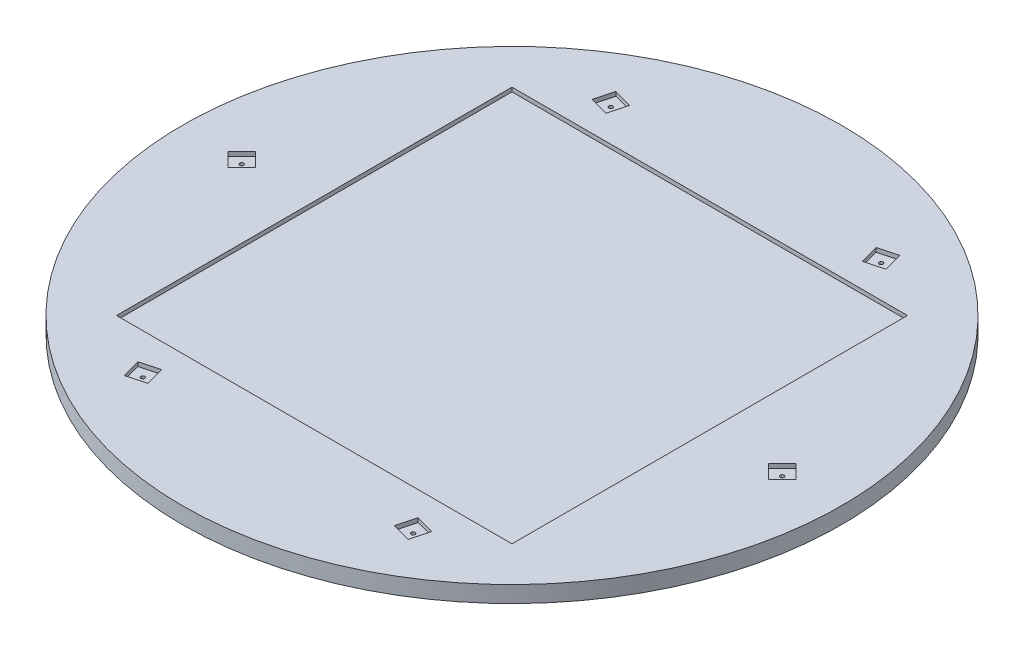
SolidWorks part; units mm, degrees
material "Balsa"
ref_plane "Front Plane" through (0, 0, 0) normal (0, 0, 1) x (1, 0, 0)
ref_plane "Top Plane" through (0, 0, 0) normal (0, 1, 0) x (1, 0, 0)
ref_plane "Right Plane" through (0, 0, 0) normal (1, 0, 0) x (0, 0, -1)
sketch "Sketch1" plane through (0, 0, 0) normal (0, 1, 0) x (1, 0, 0)
  circle A0 centre (0, 0) radius 254
  dimension "D1" = 508
extrude "Boss-Extrude1" add sketch "Sketch1" along normal blind 12.7
sketch "Sketch2" plane through (0, 12.7, 0) normal (0, 1, 0) x (1, 0, 0)
  line L1 (-152.4, -152.4) -> (152.4, -152.4)
  line L2 (-152.4, -152.4) -> (-152.4, 152.4)
  line L3 (-152.4, 152.4) -> (152.4, 152.4)
  line L4 (152.4, -152.4) -> (152.4, 152.4)
  line L5 (-152.4, -152.4) -> (152.4, 152.4) construction
  line L6 (-152.4, 152.4) -> (152.4, -152.4) construction
  point P0 (0, 0)
  dimension "D1" = 304.8
  dimension "D2" = 304.8
extrude "Cut-Extrude1" cut sketch "Sketch2" against normal blind 3.175
sketch "Sketch3" plane through (0, 12.7, 0) normal (0, 1, 0) x (1, 0, 0)
  line L0 (0, 0) -> (104.14, 180.3758) construction
  line L6 (94.9544, 185.6791) -> (113.3256, 175.0725) construction
  line L7 (98.8367, 171.1902) -> (94.9544, 185.6791)
  line L27 (94.9544, 185.6791) -> (109.4433, 189.5614)
  line L28 (109.4433, 189.5614) -> (113.3256, 175.0725)
  line L29 (113.3256, 175.0725) -> (98.8367, 171.1902)
  line L30 (109.4433, 189.5614) -> (98.8367, 171.1902) construction
  line L31 (208.28, 10.6066) -> (218.8866, 0)
  line L32 (197.6734, 0) -> (208.28, 10.6066)
  line L33 (218.8866, 0) -> (208.28, -10.6066)
  line L34 (208.28, -10.6066) -> (197.6734, 0)
  line L35 (113.3256, -175.0725) -> (109.4433, -189.5614)
  line L36 (98.8367, -171.1902) -> (113.3256, -175.0725)
  line L37 (109.4433, -189.5614) -> (94.9544, -185.6791)
  line L38 (94.9544, -185.6791) -> (98.8367, -171.1902)
  line L39 (-94.9544, -185.6791) -> (-109.4433, -189.5614)
  line L40 (-98.8367, -171.1902) -> (-94.9544, -185.6791)
  line L41 (-109.4433, -189.5614) -> (-113.3256, -175.0725)
  line L42 (-113.3256, -175.0725) -> (-98.8367, -171.1902)
  line L43 (-208.28, -10.6066) -> (-218.8866, 0)
  line L44 (-197.6734, 0) -> (-208.28, -10.6066)
  line L45 (-218.8866, 0) -> (-208.28, 10.6066)
  line L46 (-208.28, 10.6066) -> (-197.6734, 0)
  line L47 (-113.3256, 175.0725) -> (-109.4433, 189.5614)
  line L48 (-98.8367, 171.1902) -> (-113.3256, 175.0725)
  line L49 (-109.4433, 189.5614) -> (-94.9544, 185.6791)
  line L50 (-94.9544, 185.6791) -> (-98.8367, 171.1902)
  point P5 (104.14, 180.3758)
  point P6 (104.14, 180.3758)
  point P11 (-101.208, 212.9416)
  point P30 (0, 0)
  point P32 (0, 0)
  point P42 (0, 0)
  dimension "D1" = 208.28
  dimension "D2" = 15
  dimension "D3" = 60
  dimension "D4" = 6
extrude "Cut-Extrude2" cut sketch "Sketch3" against normal blind 3.175
sketch "Sketch4" plane through (0, 12.7, 0) normal (0, 1, 0) x (1, 0, 0)
  line L0 (104.14, 180.3758) -> (102.1989, 187.6202) construction
  line L1 (94.9544, 185.6791) -> (109.4433, 189.5614) construction
  line L2 (111.3844, 182.3169) -> (96.8956, 178.4346) construction
  line L4 (98.8367, 171.1902) -> (94.9544, 185.6791) construction
  line L5 (109.4433, 189.5614) -> (113.3256, 175.0725) construction
  circle A1 centre (104.14, 180.3758) radius 1.5
  circle A3 centre (208.28, 0) radius 1.5
  circle A4 centre (104.14, -180.3758) radius 1.5
  circle A5 centre (-104.14, -180.3758) radius 1.5
  circle A6 centre (-208.28, 0) radius 1.5
  circle A7 centre (-104.14, 180.3758) radius 1.5
  point P1 (111.3844, 182.3169)
  point P17 (0, 0)
  point P22 (104.14, 180.3758)
  dimension "D1" = 3
  dimension "D2" = 6
extrude "Cut-Extrude3" cut sketch "Sketch4" against normal through all
